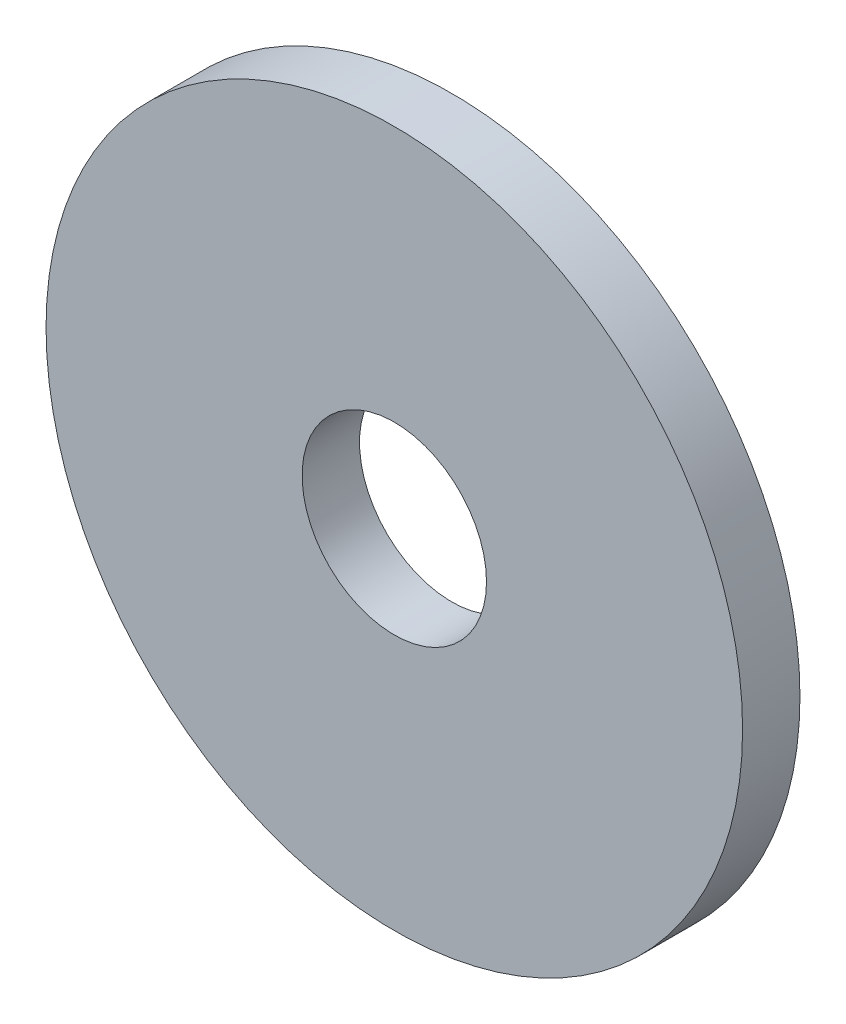
SolidWorks part; units mm, degrees
ref_plane "Přední rovina" through (0, 0, 0) normal (0, 0, 1) x (1, 0, 0)
ref_plane "Horní rovina" through (0, 0, 0) normal (0, 1, 0) x (1, 0, 0)
ref_plane "Pravá rovina" through (0, 0, 0) normal (1, 0, 0) x (0, 0, -1)
sketch "Skica1" plane through (0, 0, 0) normal (0, 0, 1) x (1, 0, 0)
  circle A0 centre (0, 0) radius 8.5
  circle A1 centre (0, 0) radius 2.25
  dimension "D1" = 17
  dimension "D2" = 4.5
extrude "Přidat vysunutím1" add sketch "Skica1" along normal blind 1.4
